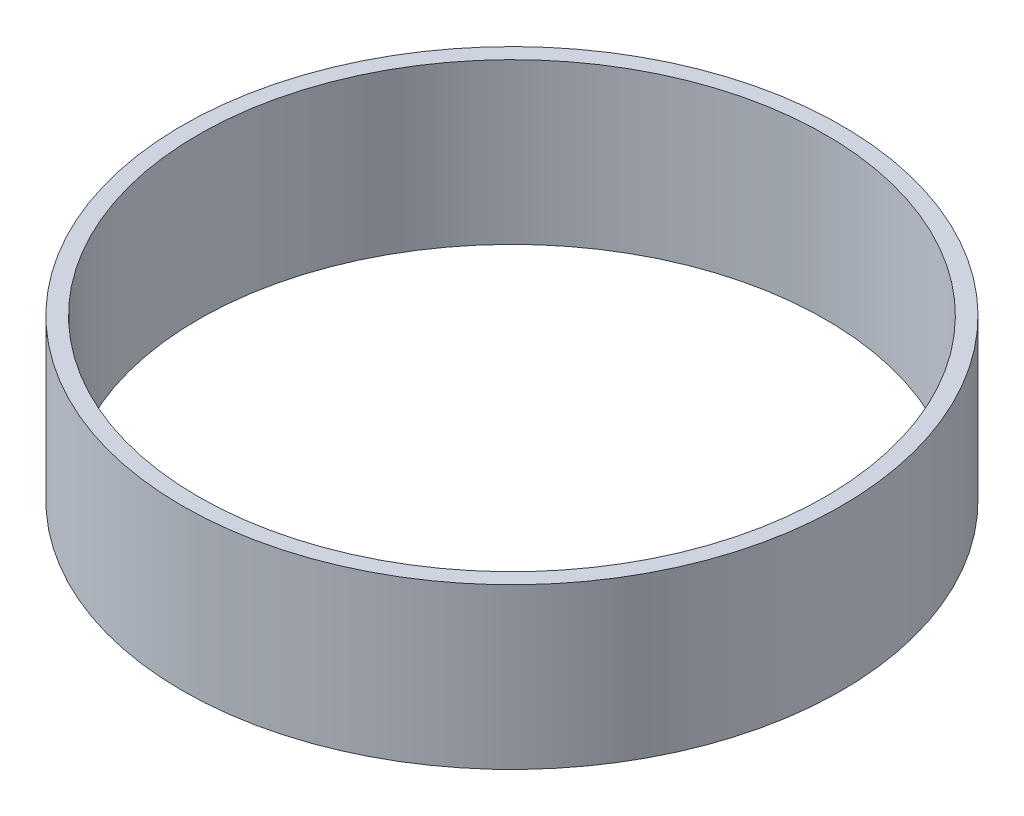
SolidWorks part; units mm, degrees
ref_plane "Front Plane" through (0, 0, 0) normal (0, 0, 1) x (1, 0, 0)
ref_plane "Top Plane" through (0, 0, 0) normal (0, 1, 0) x (1, 0, 0)
ref_plane "Right Plane" through (0, 0, 0) normal (1, 0, 0) x (0, 0, -1)
sketch "Sketch1" plane through (0, 0, 0) normal (0, 1, 0) x (1, 0, 0)
  circle A0 centre (0, 0) radius 41.2
  circle A1 centre (0, 0) radius 39.2
  dimension "D1" = 82.4
  dimension "D2" = 2
extrude "Boss-Extrude1" add sketch "Sketch1" along normal blind 20
